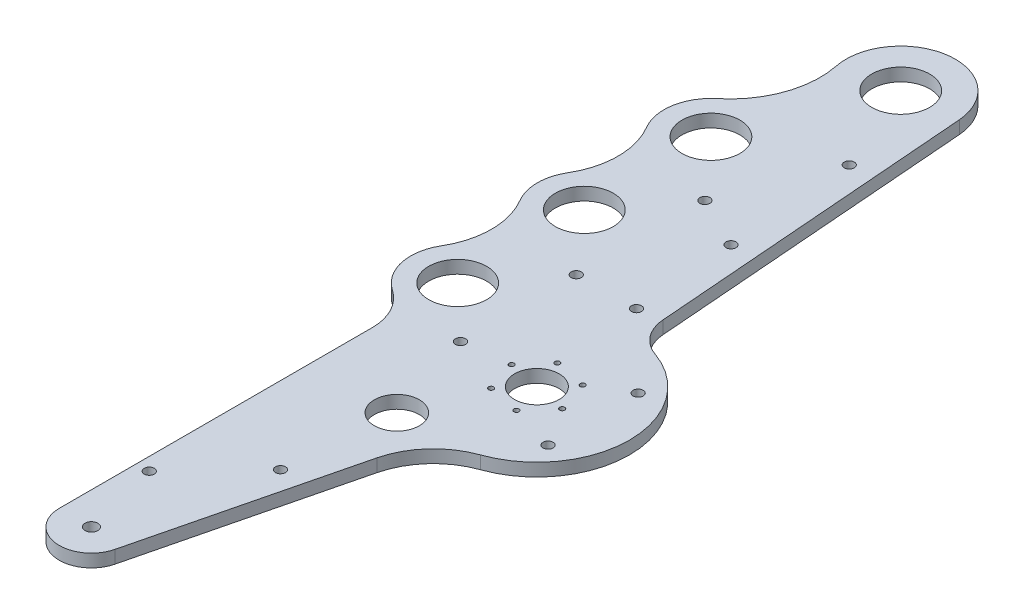
SolidWorks part; units mm, degrees
ref_plane "Front Plane" through (0, 0, 0) normal (0, 0, 1) x (1, 0, 0)
ref_plane "Top Plane" through (0, 0, 0) normal (0, 1, 0) x (1, 0, 0)
ref_plane "Right Plane" through (0, 0, 0) normal (1, 0, 0) x (0, 0, -1)
sketch "axis" plane through (0, 0, 0) normal (0, 1, 0) x (1, 0, 0)
  line L0 (0, 0) -> (0, 87.1547) construction
  line L5 (-217.7179, 0) -> (179.596, 0) construction
sketch "overall_geometry" plane through (0, 0, 0) normal (0, 1, 0) x (1, 0, 0)
  line L0 (-200217.7179, 0) -> (200179.596, 0) construction
  line L1 (-120.65, 0) -> (-95.25, 0)
  line L2 (-120.65, 0) -> (-120.65, -203.2)
  line L3 (-120.65, -203.2) -> (-95.25, -203.2)
  line L4 (-95.25, 0) -> (-95.25, -203.2)
  line L5 (0, -200000) -> (0, 200087.1547) construction
  line L6 (0, -200000) -> (0, 200087.1547) construction
  line L7 (95.25, 0) -> (95.25, -203.2)
  line L8 (120.65, -203.2) -> (95.25, -203.2)
  line L9 (120.65, 0) -> (120.65, -203.2)
  line L10 (120.65, 0) -> (95.25, 0)
  line L11 (-226.06, 25.4) -> (-212.7328, 287.4474) construction
  line L12 (-165.1, 671.7004) -> (165.1, 671.7004)
  line L13 (-165.1, 671.7004) -> (-165.1, 341.5004)
  line L14 (-165.1, 341.5004) -> (165.1, 341.5004)
  line L15 (165.1, 671.7004) -> (165.1, 341.5004)
  line L20 (-177.8, 25.4) -> (177.8, 25.4)
  line L22 (-120.65, 0) -> (120.65, 0)
  line L24 (-185.5973, 220.9114) -> (-185.5973, 95.8926) construction
  line L25 (-151.4074, 1163.1674) -> (-151.4074, 832.9674)
  line L26 (-151.4074, 1163.1674) -> (127.9926, 1163.1674)
  line L27 (-151.4074, 832.9674) -> (127.9926, 832.9674)
  line L28 (127.9926, 1163.1674) -> (127.9926, 832.9674)
  line L29 (226.06, 25.4) -> (212.7328, 287.4474) construction
  line L30 (185.5973, 220.9114) -> (185.5973, 95.8926) construction
  line L31 (-177.8, 25.4) -> (-177.8, 0)
  line L33 (-177.8, 0) -> (-120.65, 0)
  line L36 (177.8, 25.4) -> (177.8, 0)
  line L37 (177.8, 0) -> (120.65, 0)
  line L38 (-226.06, 25.4) -> (-199.4632, -98.7838) construction
  line L39 (-225.8637, -101.5998) -> (-21.1081, -38.1) construction
  line L40 (-182.439, -93.8737) -> (-226.06, 25.4) construction
  line L41 (-226.06, 25.4) -> (-225.8637, -101.5998) construction
  line L42 (-182.439, -93.8737) -> (-21.1081, -38.1) construction
  line L43 (182.439, -93.8737) -> (226.06, 25.4) construction
  line L44 (226.06, 25.4) -> (225.8637, -101.5998) construction
  line L45 (226.06, 25.4) -> (199.4632, -98.7838) construction
  line L46 (182.439, -93.8737) -> (21.1081, -38.1) construction
  line L47 (225.8637, -101.5998) -> (21.1081, -38.1) construction
  circle A0 centre (-226.06, 25.4) radius 11.1125
  circle A1 centre (-185.5973, 95.8926) radius 25.4
  circle A2 centre (-185.5973, 158.402) radius 25.4
  circle A3 centre (-185.5973, 220.9114) radius 25.4
  circle A5 centre (-212.7328, 287.4474) radius 38.1
  circle A6 centre (-185.5973, 95.8926) radius 14.2875
  circle A7 centre (-185.5973, 158.402) radius 14.2875
  circle A8 centre (-185.5973, 220.9114) radius 14.2875
  circle A10 centre (-212.7328, 287.4474) radius 14.2875
  circle A11 centre (212.7328, 287.4474) radius 14.2875
  circle A12 centre (185.5973, 220.9114) radius 14.2875
  circle A13 centre (185.5973, 158.402) radius 14.2875
  circle A14 centre (185.5973, 95.8926) radius 14.2875
  circle A15 centre (212.7328, 287.4474) radius 38.1
  circle A16 centre (185.5973, 220.9114) radius 25.4
  circle A17 centre (185.5973, 158.402) radius 25.4
  circle A18 centre (185.5973, 95.8926) radius 25.4
  circle A19 centre (226.06, 25.4) radius 11.1125
  circle A20 centre (-249.465, 71.12) radius 26.67
  circle A21 centre (249.465, 71.12) radius 26.67
  circle A22 centre (-199.4632, -98.7838) radius 3.175
  circle A23 centre (199.4632, -98.7838) radius 3.175
  point P16 (0, 671.7004)
  point P55 (0, 25.4)
  dimension "D8" = 22.225
  dimension "D9" = 25.4
  dimension "D10" = 76.2
  dimension "D11" = 14.2875
  dimension "D19" = 53.34
  dimension "D30" = 6.35
  dimension "D1" = 203.2
  dimension "D2" = 25.4
  dimension "D3" = 95.25
  dimension "D4" = 330.2
  dimension "D5" = 330.2
  dimension "D6" = 214.376
  dimension "D7" = 25.4
  dimension "D12" = 30.48
  dimension "D13" = 36.83
  dimension "D14" = 71.8566
  dimension "D15" = 62.5094
  dimension "D16" = 62.5094
  dimension "D17" = 81.28
  dimension "D18" = 279.4
  dimension "D20" = 330.2
  dimension "D21" = 105.41
  dimension "D22" = 68.5038
  dimension "D23" = 45.72
  dimension "D24" = 177.8
  dimension "D25" = 165
  dimension "D26" = 8
  dimension "D27" = 12
  dimension "D28" = 127
  dimension "D29" = 38.1
sketch "claw_features" plane through (0, 0, 0) normal (0, 1, 0) x (1, 0, 0)
  circle A0 centre (-212.7328, 287.4474) radius 14.2875 construction
  circle A1 centre (-212.7328, 287.4474) radius 38.1 construction
  circle A2 centre (-185.5973, 95.8926) radius 25.4 construction
  circle A3 centre (-185.5973, 158.402) radius 25.4 construction
  circle A4 centre (-185.5973, 220.9114) radius 25.4 construction
  circle A5 centre (-185.5973, 220.9114) radius 14.2875 construction
  circle A6 centre (-185.5973, 158.402) radius 14.2875 construction
  circle A7 centre (-185.5973, 95.8926) radius 14.2875 construction
  circle A8 centre (-249.465, 71.12) radius 26.67 construction
  circle A9 centre (-226.06, 25.4) radius 11.1125 construction
  circle A10 centre (-199.4632, -98.7838) radius 3.175 construction
  circle A11 centre (-212.7328, 287.4474) radius 14.2875
  circle A12 centre (-212.7328, 287.4474) radius 38.1
  circle A13 centre (-185.5973, 95.8926) radius 25.4
  circle A14 centre (-185.5973, 158.402) radius 25.4
  circle A15 centre (-185.5973, 220.9114) radius 25.4
  circle A16 centre (-185.5973, 220.9114) radius 14.2875
  circle A17 centre (-185.5973, 158.402) radius 14.2875
  circle A18 centre (-185.5973, 95.8926) radius 14.2875
  circle A19 centre (-249.465, 71.12) radius 26.67
  circle A20 centre (-226.06, 25.4) radius 11.1125
  circle A21 centre (-199.4632, -98.7838) radius 3.175
sketch "mounting_plates_features" plane through (0, 0, 0) normal (0, 1, 0) x (1, 0, 0)
  line L0 (-200217.7179, 0) -> (200179.596, 0) construction
  line L1 (177.8, 25.4) -> (177.8, 0) construction
  line L2 (120.65, 0) -> (120.65, -203.2) construction
  line L3 (95.25, 0) -> (95.25, -203.2) construction
  line L4 (120.65, -203.2) -> (95.25, -203.2) construction
  line L5 (-120.65, -203.2) -> (-95.25, -203.2) construction
  line L6 (-95.25, 0) -> (-95.25, -203.2) construction
  line L7 (-177.8, 25.4) -> (177.8, 25.4) construction
  line L8 (-177.8, 25.4) -> (-177.8, 0) construction
  line L9 (-120.65, 0) -> (-120.65, -203.2) construction
  line L10 (-200217.7179, 0) -> (200179.596, 0)
  line L11 (177.8, 25.4) -> (177.8, 0)
  line L12 (120.65, 0) -> (120.65, -203.2)
  line L13 (95.25, 0) -> (95.25, -203.2)
  line L14 (120.65, -203.2) -> (95.25, -203.2)
  line L15 (-120.65, -203.2) -> (-95.25, -203.2)
  line L16 (-95.25, 0) -> (-95.25, -203.2)
  line L17 (-177.8, 25.4) -> (177.8, 25.4)
  line L18 (-177.8, 25.4) -> (-177.8, 0)
  line L19 (-120.65, 0) -> (-120.65, -203.2)
  circle A0 centre (-226.06, 25.4) radius 11.1125 construction
  circle A1 centre (-226.06, 25.4) radius 11.1125
  circle A2 centre (226.06, 25.4) radius 11.1125 construction
  circle A3 centre (226.06, 25.4) radius 11.1125
  point P0 (-21.1081, -38.1)
  point P20 (21.1081, -38.1)
sketch "Sketch2" plane through (0, 0, 0) normal (0, 1, 0) x (1, 0, 0)
  line L0 (239.6381, 289.5518) -> (252.063, 130.7002)
  line L1 (240.4082, 1.1956) -> (214.8786, -102.5762)
  line L2 (183.5882, 55.7863) -> (183.5882, -98.7838)
  line L3 (264.705, 114.2252) -> (264.705, 28.0148) construction
  circle A0 centre (185.5973, 95.8926) radius 14.2875 construction
  circle A1 centre (185.5973, 158.402) radius 14.2875 construction
  circle A2 centre (185.5973, 220.9114) radius 14.2875 construction
  circle A3 centre (185.5973, 95.8926) radius 14.2875
  circle A4 centre (185.5973, 158.402) radius 14.2875
  circle A5 centre (185.5973, 220.9114) radius 14.2875
  arc A6 (170.9048, 238.837) -> (165.6613, 209.0897) centre (185.5973, 220.9114) ccw
  arc A7 (165.6613, 170.2237) -> (165.6613, 146.5803) centre (185.5973, 158.402) ccw
  arc A8 (165.6613, 107.7143) -> (172.5198, 76.7569) centre (185.5973, 95.8926) ccw
  circle A9 centre (212.7328, 287.4474) radius 14.2875 construction
  circle A10 centre (212.7328, 287.4474) radius 14.2875
  arc A11 (239.6381, 289.5518) -> (186.2863, 282.0707) centre (212.7328, 287.4474) ccw
  circle A12 centre (249.465, 71.12) radius 26.67 construction
  circle A13 centre (249.465, 71.12) radius 26.67 construction
  arc A14 (264.705, 28.0148) -> (264.705, 114.2252) centre (249.465, 71.12) ccw
  arc A15 (186.2863, 282.0707) -> (170.9048, 238.837) centre (142.7274, 273.2149) cw
  arc A16 (165.6613, 209.0897) -> (165.6613, 170.2237) centre (132.8898, 189.6567) cw
  arc A17 (165.6613, 146.5803) -> (165.6613, 107.7143) centre (132.8898, 127.1473) cw
  arc A18 (252.063, 130.7002) -> (264.705, 114.2252) centre (271.055, 132.1857) ccw
  arc A19 (264.705, 28.0148) -> (240.4082, 1.1956) centre (277.405, -7.9063) ccw
  arc A20 (172.5198, 76.7569) -> (183.5882, 55.7863) centre (158.1882, 55.7863) cw
  circle A21 centre (199.4632, -98.7838) radius 3.175 construction
  circle A22 centre (199.4632, -98.7838) radius 3.175
  arc A23 (183.5882, -98.7838) -> (214.8786, -102.5762) centre (199.4632, -98.7838) ccw
  circle A24 centre (249.465, 71.12) radius 14.2875 construction
  circle A25 centre (212.7328, 287.4474) radius 26.9875 construction
  circle A26 centre (185.5973, 220.9114) radius 23.1775 construction
  circle A27 centre (185.5973, 158.402) radius 23.1775 construction
  circle A28 centre (185.5973, 95.8926) radius 23.1775 construction
  circle A29 centre (249.465, 71.12) radius 45.72 construction
  circle A30 centre (199.4632, -98.7838) radius 15.875 construction
  circle A31 centre (249.465, 71.12) radius 11
  circle A32 centre (226.06, 25.4) radius 11.1125 construction
  circle A33 centre (226.06, 25.4) radius 11.1125
  point P10 (206.2348, 158.402)
  point P12 (206.2348, 95.8926)
  point P14 (288.835, 71.12)
  point P19 (206.2348, 220.9114)
  point P24 (209.7865, -95.6276)
  point P53 (239.7203, 287.4474)
  dimension "D5" = 19.05
  dimension "D6" = 38.1
  dimension "D8" = 38.1
  dimension "D9" = 38.1
  dimension "D10" = 25.4
  dimension "D11" = 44.45
  dimension "D12" = 22
  dimension "D7" = 15.24
  dimension "D1" = 8.89
  dimension "D2" = 12.7
  dimension "D3" = 19.05
  dimension "D4" = 12.7
extrude "Boss-Extrude1" add sketch "Sketch2" along normal blind 6.35
sketch "Sketch3" plane through (0, 6.35, 0) normal (0, 1, 0) x (1, 0, 0)
  arc A1 (233.5364, 73.0796) -> (234.0339, 75.5295) centre (233.7852, 74.3046) ccw construction
  arc A2 (234.0339, 75.5295) -> (233.5364, 73.0796) centre (233.7852, 74.3046) ccw construction
  arc A3 (233.5364, 73.0796) -> (234.0339, 75.5295) centre (233.7852, 74.3046) ccw
  arc A4 (234.0339, 75.5295) -> (233.5364, 73.0796) centre (233.7852, 74.3046) ccw
  arc A5 (254.7959, 57.1735) -> (254.2983, 54.7236) centre (254.5471, 55.9485) ccw construction
  arc A6 (254.2983, 54.7236) -> (254.7959, 57.1735) centre (254.5471, 55.9485) ccw construction
  arc A7 (264.8961, 66.7105) -> (265.3937, 69.1604) centre (265.1449, 67.9354) ccw construction
  arc A8 (265.3937, 69.1604) -> (264.8961, 66.7105) centre (265.1449, 67.9354) ccw construction
  arc A9 (259.8141, 81.8819) -> (260.3117, 84.3319) centre (260.0629, 83.1069) ccw construction
  arc A10 (260.3117, 84.3319) -> (259.8141, 81.8819) centre (260.0629, 83.1069) ccw construction
  arc A11 (244.1342, 85.0665) -> (244.6318, 87.5164) centre (244.383, 86.2915) ccw construction
  arc A12 (244.6318, 87.5164) -> (244.1342, 85.0665) centre (244.383, 86.2915) ccw construction
  arc A13 (254.7959, 57.1735) -> (254.2983, 54.7236) centre (254.5471, 55.9485) ccw
  arc A14 (254.2983, 54.7236) -> (254.7959, 57.1735) centre (254.5471, 55.9485) ccw
  arc A15 (264.8961, 66.7105) -> (265.3937, 69.1604) centre (265.1449, 67.9354) ccw
  arc A16 (265.3937, 69.1604) -> (264.8961, 66.7105) centre (265.1449, 67.9354) ccw
  arc A17 (259.8141, 81.8819) -> (260.3117, 84.3319) centre (260.0629, 83.1069) ccw
  arc A18 (260.3117, 84.3319) -> (259.8141, 81.8819) centre (260.0629, 83.1069) ccw
  arc A19 (244.1342, 85.0665) -> (244.6318, 87.5164) centre (244.383, 86.2915) ccw
  arc A20 (244.6318, 87.5164) -> (244.1342, 85.0665) centre (244.383, 86.2915) ccw
  arc A21 (239.116, 60.3581) -> (238.6184, 57.9081) centre (238.8672, 59.1331) ccw construction
  arc A22 (238.6184, 57.9081) -> (239.116, 60.3581) centre (238.8672, 59.1331) ccw construction
  arc A23 (239.116, 60.3581) -> (238.6184, 57.9081) centre (238.8672, 59.1331) ccw
  arc A24 (238.6184, 57.9081) -> (239.116, 60.3581) centre (238.8672, 59.1331) ccw
extrude "Cut-Extrude1" cut sketch "Sketch3" against normal through all
sketch "Sketch4" plane through (0, 6.35, 0) normal (0, 1, 0) x (1, 0, 0)
  line L0 (231.7828, 242.9974) -> (236.7345, 179.6907) construction
  line L1 (252.063, 130.7002) -> (239.6381, 289.5518) construction
  line L2 (236.7345, 179.6907) -> (240.6958, 129.0454) construction
  line L3 (277.224, 93.345) -> (277.224, 48.895) construction
  line L4 (183.5882, 55.7863) -> (183.5882, -98.7838) construction
  circle A0 centre (231.7828, 242.9974) radius 2.4892
  circle A1 centre (211.3345, 192.1974) radius 2.4892
  circle A2 centre (236.7345, 179.6907) radius 2.4892
  circle A3 centre (211.3345, 128.6974) radius 2.4892
  circle A4 centre (211.3345, 71.5474) radius 2.4892
  circle A5 centre (221.6882, -27.6638) radius 2.4892
  circle A6 centre (189.9382, -60.6838) radius 2.4892
  circle A7 centre (277.224, 93.345) radius 2.4892
  circle A8 centre (277.224, 48.895) radius 2.4892
  circle A9 centre (212.7328, 287.4474) radius 14.2875 construction
  circle A10 centre (240.6958, 129.0454) radius 2.4892
  circle A11 centre (249.465, 71.12) radius 35.56 construction
  circle A12 centre (199.4632, -98.7838) radius 3.175 construction
  dimension "D1" = 4.9784
  dimension "D9" = 63.5
  dimension "D11" = 71.12
  dimension "D14" = 31.75
  dimension "D15" = 33.02
  dimension "D16" = 38.1
  dimension "D2" = 50.8
  dimension "D3" = 25.4
  dimension "D4" = 25.4
  dimension "D5" = 44.45
  dimension "D6" = 19.05
  dimension "D7" = 63.5
  dimension "D8" = 50.8
  dimension "D10" = 57.15
  dimension "D12" = 44.45
  dimension "D13" = 6.35
extrude "Cut-Extrude2" cut sketch "Sketch4" against normal through all
